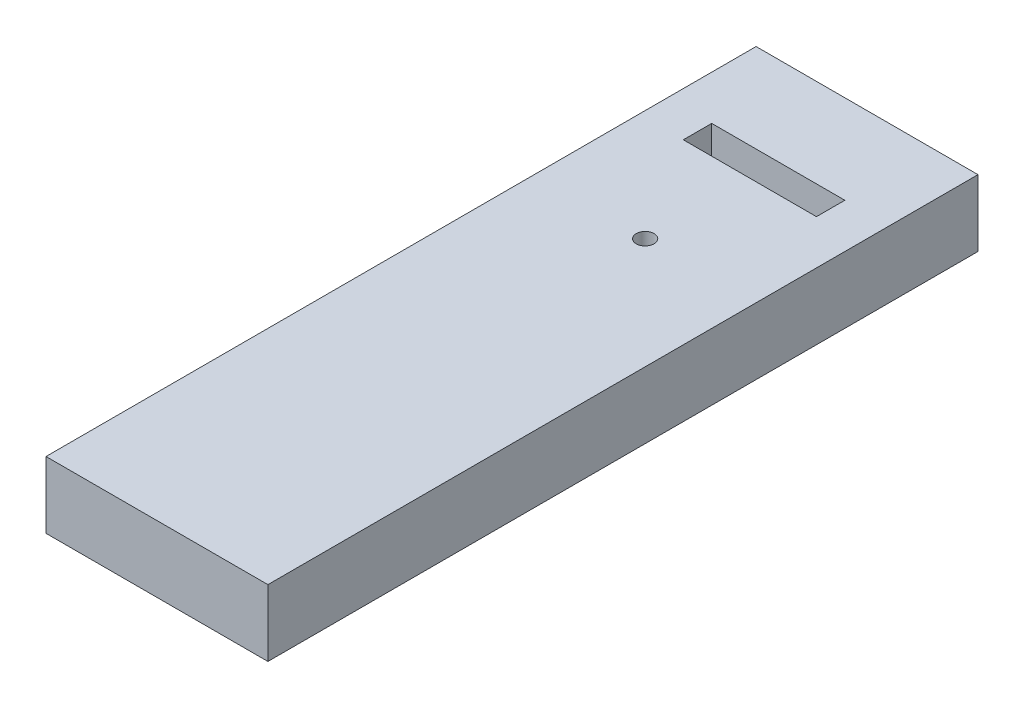
SolidWorks part; units mm, degrees
ref_plane "Front Plane" through (0, 0, 0) normal (0, 0, 1) x (1, 0, 0)
ref_plane "Top Plane" through (0, 0, 0) normal (0, 1, 0) x (1, 0, 0)
ref_plane "Right Plane" through (0, 0, 0) normal (1, 0, 0) x (0, 0, -1)
sketch "Sketch1" plane through (0, 0, 0) normal (0, 1, 0) x (1, 0, 0)
  line L1 (-31.75, -101.6) -> (31.75, -101.6)
  line L2 (-31.75, -101.6) -> (-31.75, 101.6)
  line L3 (-31.75, 101.6) -> (31.75, 101.6)
  line L4 (31.75, -101.6) -> (31.75, 101.6)
  line L5 (-31.75, -101.6) -> (31.75, 101.6) construction
  line L6 (-31.75, 101.6) -> (31.75, -101.6) construction
  point P0 (0, 0)
  dimension "D1" = 63.5
  dimension "D2" = 203.2
extrude "Boss-Extrude1" add sketch "Sketch1" along normal blind 19.05
sketch "Sketch2" plane through (0, 0, -101.6) normal (0, 0, -1) x (-1, 0, 0)
  line L1 (-31.75, 0) -> (31.75, 0) construction
  circle A0 centre (0, 0) radius 4.7625
  dimension "D1" = 9.525
extrude "Cut-Extrude1" cut sketch "Sketch2" against normal blind 25.4
ref_plane "Plane1" through (0, 0, 0) normal (0, -1, 0) x (-1, 0, 0)
sketch "Sketch3" plane through (0, 0, 0) normal (0, -1, 0) x (-1, 0, 0)
  line L0 (4.7625, 76.2) -> (-4.7625, 76.2) construction
  line L1 (-20.6375, -96.8375) -> (20.6375, -96.8375)
  line L2 (-26.9875, -90.4875) -> (-26.9875, 41.402)
  line L3 (-23.8125, 76.2) -> (23.8125, 76.2)
  line L4 (26.9875, -90.4875) -> (26.9875, 41.402)
  line L5 (23.8125, 68.072) -> (-23.8125, 68.072)
  line L6 (20.6375, 47.752) -> (-20.6375, 47.752)
  line L7 (26.9875, 71.247) -> (26.9875, 73.025)
  line L8 (-26.9875, 71.247) -> (-26.9875, 73.025)
  line L14 (4.7625, 101.6) -> (4.7625, 76.2)
  line L15 (4.7625, 76.2) -> (-4.7625, 76.2)
  line L16 (-4.7625, 76.2) -> (-4.7625, 101.6)
  line L17 (-4.7625, 101.6) -> (-31.75, 101.6)
  line L18 (-31.75, 101.6) -> (-31.75, -101.6)
  line L19 (-31.75, -101.6) -> (31.75, -101.6)
  line L20 (31.75, -101.6) -> (31.75, 101.6)
  line L21 (31.75, 101.6) -> (4.7625, 101.6)
  line L25 (-4.7625, 101.6) -> (-31.75, 101.6) construction
  line L26 (-31.75, 101.6) -> (-31.75, -101.6) construction
  line L27 (-31.75, -101.6) -> (31.75, -101.6) construction
  line L28 (31.75, -101.6) -> (31.75, 101.6) construction
  line L29 (31.75, 101.6) -> (4.7625, 101.6) construction
  arc A0 (-26.9875, -90.4875) -> (-20.6375, -96.8375) centre (-20.6375, -90.4875) ccw
  arc A1 (20.6375, -96.8375) -> (26.9875, -90.4875) centre (20.6375, -90.4875) ccw
  arc A2 (26.9875, 73.025) -> (23.8125, 76.2) centre (23.8125, 73.025) ccw
  arc A3 (-23.8125, 76.2) -> (-26.9875, 73.025) centre (-23.8125, 73.025) ccw
  arc A4 (20.6375, 47.752) -> (26.9875, 41.402) centre (20.6375, 41.402) cw
  arc A5 (-20.6375, 47.752) -> (-26.9875, 41.402) centre (-20.6375, 41.402) ccw
  arc A6 (-23.8125, 68.072) -> (-26.9875, 71.247) centre (-23.8125, 71.247) cw
  arc A7 (23.8125, 68.072) -> (26.9875, 71.247) centre (23.8125, 71.247) ccw
  point P0 (0, 0)
  point P33 (-26.9875, 68.072)
  point P36 (26.9875, 68.072)
  dimension "D5" = 6.35
  dimension "D6" = 8.128
  dimension "D8" = 6.35
  dimension "D9" = 3.175
  dimension "D2" = 9.525
  dimension "D3" = 9.525
  dimension "D4" = 9.525
  dimension "D7" = 20.32
  dimension "D1" = 0
extrude "Cut-Extrude2" cut sketch "Sketch3" against normal blind 9.525
sketch "Sketch5" plane through (0, 0, 0) normal (0, 1, 0) x (1, 0, 0)
  line L0 (4.7625, 76.2) -> (23.8125, 76.2) construction
  line L1 (19.05, 76.2) -> (-19.05, 76.2)
  line L2 (19.05, 76.2) -> (19.05, 68.072)
  line L3 (19.05, 68.072) -> (-19.05, 68.072)
  line L4 (-19.05, 76.2) -> (-19.05, 68.072)
  line L5 (0, 0) -> (0, 132.0825) construction
  dimension "D1" = 8.128
  dimension "D2" = 38.1
extrude "Cut-Extrude4" cut sketch "Sketch5" along normal through all
sketch "Sketch6" plane through (0, 0, 0) normal (0, 1, 0) x (1, 0, 0)
  line L1 (-26.9875, 71.247) -> (26.9875, 71.247)
  line L2 (-26.9875, 71.247) -> (-26.9875, 41.402)
  line L3 (-26.9875, 41.402) -> (26.9875, 41.402)
  line L4 (26.9875, 71.247) -> (26.9875, 41.402)
extrude "Cut-Extrude5" cut sketch "Sketch6" along normal blind 2.159
hole_wizard "1/4-20 Tapped Hole1" positions "Sketch8" profile "Sketch7" tap size "1/4-20" standard "ANSI Inch"
sketch "Sketch8" plane through (-11.0345, 19.05, 14.5475) normal (0, -1, 0) x (-1, 0, 0)
  line L0 (12.778, 90.7475) -> (-6.272, 90.7475) construction
  point P0 (-11.0345, 52.6475)
  dimension "D1" = 38.1
  dimension "D2" = 0
sketch "Sketch7" plane through (0, 19.05, -38.1) normal (1, 0, 0) x (0, 0, 1)
  line L0 (0, 0) -> (0, 20.5838)
  line L1 (0, 20.5838) -> (2.5527, 19.05)
  line L2 (2.5527, 19.05) -> (2.5527, 0)
  line L5 (2.5527, 0) -> (0, 0)
  line L10 (0, 20.5838) -> (-2.5527, 19.05) construction
  line L11 (0, -6.35) -> (0, 107.95) construction
  dimension "Tap Drill Dia." = 5.1054
  dimension "Tap Drill Depth" = 19.05
  dimension "Drill Angle" = 118
cosmetic thread "Hole Thread2" parameters "D1"=9.525, "D2"=6.35
